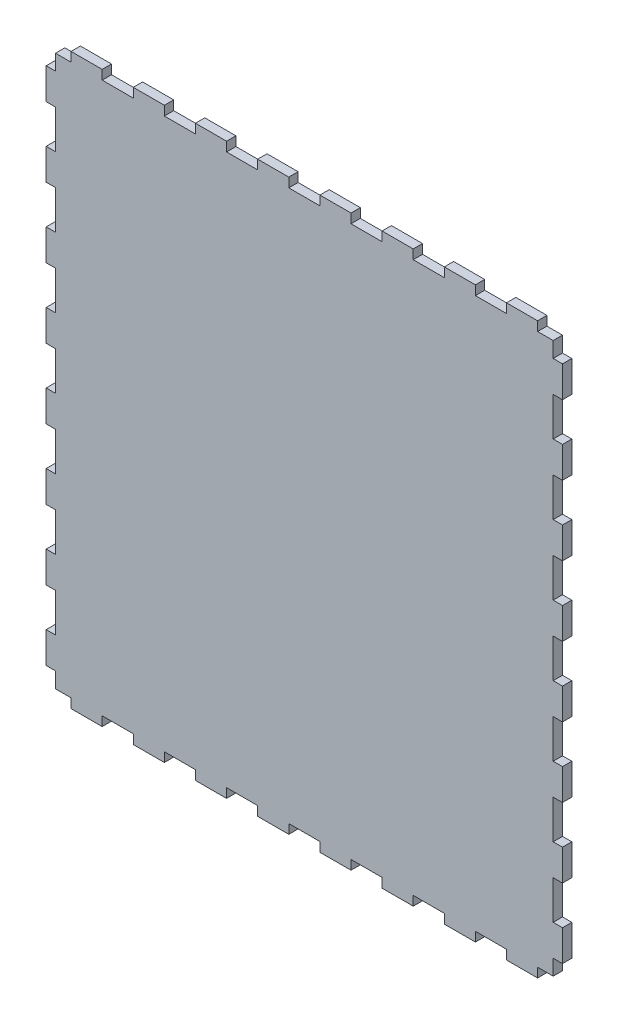
SolidWorks part; units mm, degrees
ref_plane "Front Plane" through (0, 0, 0) normal (0, 0, 1) x (1, 0, 0)
ref_plane "Top Plane" through (0, 0, 0) normal (0, 1, 0) x (1, 0, 0)
ref_plane "Right Plane" through (0, 0, 0) normal (1, 0, 0) x (0, 0, -1)
sketch "Sketch1" plane through (0, 0, 0) normal (0, 0, 1) x (1, 0, 0)
  line L0 (-39.6781, 48.7508) -> (-39.6781, 45.7508)
  line L1 (-64.6781, 45.7508) -> (-59.6781, 45.7508)
  line L2 (-64.6781, 45.7508) -> (-64.6781, 40.7508)
  line L3 (-64.6781, -131.2492) -> (-59.6781, -131.2492)
  line L4 (95.3219, 45.7508) -> (95.3219, 40.7508)
  line L5 (-59.6781, 48.7508) -> (-49.6781, 48.7508)
  line L6 (-59.6781, 48.7508) -> (-59.6781, 45.7508)
  line L8 (-49.6781, 48.7508) -> (-49.6781, 45.7508)
  line L9 (-39.6781, 48.7508) -> (-29.6781, 48.7508)
  line L10 (-29.6781, 48.7508) -> (-29.6781, 45.7508)
  line L12 (-19.6781, 48.7508) -> (-19.6781, 45.7508)
  line L13 (-19.6781, 48.7508) -> (-9.6781, 48.7508)
  line L14 (-9.6781, 48.7508) -> (-9.6781, 45.7508)
  line L16 (0.3219, 48.7508) -> (0.3219, 45.7508)
  line L17 (0.3219, 48.7508) -> (10.3219, 48.7508)
  line L18 (10.3219, 48.7508) -> (10.3219, 45.7508)
  line L20 (20.3219, 48.7508) -> (20.3219, 45.7508)
  line L21 (20.3219, 48.7508) -> (30.3219, 48.7508)
  line L22 (30.3219, 48.7508) -> (30.3219, 45.7508)
  line L24 (40.3219, 48.7508) -> (40.3219, 45.7508)
  line L25 (40.3219, 48.7508) -> (50.3219, 48.7508)
  line L26 (50.3219, 48.7508) -> (50.3219, 45.7508)
  line L28 (60.3219, 48.7508) -> (60.3219, 45.7508)
  line L29 (60.3219, 48.7508) -> (70.3219, 48.7508)
  line L30 (70.3219, 48.7508) -> (70.3219, 45.7508)
  line L32 (80.3219, 48.7508) -> (80.3219, 45.7508)
  line L33 (80.3219, 48.7508) -> (90.3219, 48.7508)
  line L34 (90.3219, 48.7508) -> (90.3219, 45.7508)
  line L37 (-64.6781, 40.7508) -> (-67.6781, 40.7508)
  line L39 (-64.6781, 30.7508) -> (-67.6781, 30.7508)
  line L40 (-67.6781, 40.7508) -> (-67.6781, 30.7508)
  line L41 (-64.6781, 18.3222) -> (-67.6781, 18.3222)
  line L42 (-67.6781, 18.3222) -> (-67.6781, 8.3222)
  line L43 (-64.6781, 8.3222) -> (-67.6781, 8.3222)
  line L45 (-64.6781, -4.1063) -> (-67.6781, -4.1063)
  line L46 (-67.6781, -4.1063) -> (-67.6781, -14.1063)
  line L47 (-64.6781, -14.1063) -> (-67.6781, -14.1063)
  line L49 (-64.6781, -26.5349) -> (-67.6781, -26.5349)
  line L50 (-67.6781, -26.5349) -> (-67.6781, -36.5349)
  line L51 (-64.6781, -36.5349) -> (-67.6781, -36.5349)
  line L53 (-64.6781, -48.9635) -> (-67.6781, -48.9635)
  line L54 (-67.6781, -48.9635) -> (-67.6781, -58.9635)
  line L55 (-64.6781, -58.9635) -> (-67.6781, -58.9635)
  line L57 (-64.6781, -71.3921) -> (-67.6781, -71.3921)
  line L58 (-67.6781, -71.3921) -> (-67.6781, -81.3921)
  line L59 (-64.6781, -81.3921) -> (-67.6781, -81.3921)
  line L61 (-64.6781, -93.8206) -> (-67.6781, -93.8206)
  line L62 (-67.6781, -93.8206) -> (-67.6781, -103.8206)
  line L63 (-64.6781, -103.8206) -> (-67.6781, -103.8206)
  line L65 (-64.6781, -116.2492) -> (-67.6781, -116.2492)
  line L66 (-67.6781, -116.2492) -> (-67.6781, -126.2492)
  line L67 (-64.6781, -126.2492) -> (-67.6781, -126.2492)
  line L68 (-39.6781, -134.2492) -> (-39.6781, -131.2492)
  line L69 (-59.6781, -134.2492) -> (-49.6781, -134.2492)
  line L70 (-59.6781, -134.2492) -> (-59.6781, -131.2492)
  line L72 (-49.6781, -134.2492) -> (-49.6781, -131.2492)
  line L73 (-39.6781, -134.2492) -> (-29.6781, -134.2492)
  line L74 (-29.6781, -134.2492) -> (-29.6781, -131.2492)
  line L76 (-19.6781, -134.2492) -> (-19.6781, -131.2492)
  line L77 (-19.6781, -134.2492) -> (-9.6781, -134.2492)
  line L78 (-9.6781, -134.2492) -> (-9.6781, -131.2492)
  line L80 (0.3219, -134.2492) -> (0.3219, -131.2492)
  line L81 (0.3219, -134.2492) -> (10.3219, -134.2492)
  line L82 (10.3219, -134.2492) -> (10.3219, -131.2492)
  line L84 (20.3219, -134.2492) -> (20.3219, -131.2492)
  line L85 (20.3219, -134.2492) -> (30.3219, -134.2492)
  line L86 (30.3219, -134.2492) -> (30.3219, -131.2492)
  line L88 (40.3219, -134.2492) -> (40.3219, -131.2492)
  line L89 (40.3219, -134.2492) -> (50.3219, -134.2492)
  line L90 (50.3219, -134.2492) -> (50.3219, -131.2492)
  line L92 (60.3219, -134.2492) -> (60.3219, -131.2492)
  line L93 (60.3219, -134.2492) -> (70.3219, -134.2492)
  line L94 (70.3219, -134.2492) -> (70.3219, -131.2492)
  line L96 (80.3219, -134.2492) -> (80.3219, -131.2492)
  line L97 (80.3219, -134.2492) -> (90.3219, -134.2492)
  line L98 (90.3219, -134.2492) -> (90.3219, -131.2492)
  line L101 (95.3219, 40.7508) -> (98.3219, 40.7508)
  line L103 (95.3219, 30.7508) -> (98.3219, 30.7508)
  line L104 (98.3219, 40.7508) -> (98.3219, 30.7508)
  line L105 (95.3219, 18.3222) -> (98.3219, 18.3222)
  line L106 (98.3219, 18.3222) -> (98.3219, 8.3222)
  line L107 (95.3219, 8.3222) -> (98.3219, 8.3222)
  line L109 (95.3219, -4.1063) -> (98.3219, -4.1063)
  line L110 (98.3219, -4.1063) -> (98.3219, -14.1063)
  line L111 (95.3219, -14.1063) -> (98.3219, -14.1063)
  line L113 (95.3219, -26.5349) -> (98.3219, -26.5349)
  line L114 (98.3219, -26.5349) -> (98.3219, -36.5349)
  line L115 (95.3219, -36.5349) -> (98.3219, -36.5349)
  line L117 (95.3219, -48.9635) -> (98.3219, -48.9635)
  line L118 (98.3219, -48.9635) -> (98.3219, -58.9635)
  line L119 (95.3219, -58.9635) -> (98.3219, -58.9635)
  line L121 (95.3219, -71.3921) -> (98.3219, -71.3921)
  line L122 (98.3219, -71.3921) -> (98.3219, -81.3921)
  line L123 (95.3219, -81.3921) -> (98.3219, -81.3921)
  line L125 (95.3219, -93.8206) -> (98.3219, -93.8206)
  line L126 (98.3219, -93.8206) -> (98.3219, -103.8206)
  line L127 (95.3219, -103.8206) -> (98.3219, -103.8206)
  line L129 (95.3219, -116.2492) -> (98.3219, -116.2492)
  line L130 (98.3219, -116.2492) -> (98.3219, -126.2492)
  line L131 (95.3219, -126.2492) -> (98.3219, -126.2492)
  line L132 (-49.6781, 45.7508) -> (-39.6781, 45.7508)
  line L133 (-29.6781, 45.7508) -> (-19.6781, 45.7508)
  line L134 (-9.6781, 45.7508) -> (0.3219, 45.7508)
  line L135 (30.3219, 45.7508) -> (40.3219, 45.7508)
  line L136 (10.3219, 45.7508) -> (20.3219, 45.7508)
  line L137 (50.3219, 45.7508) -> (60.3219, 45.7508)
  line L138 (70.3219, 45.7508) -> (80.3219, 45.7508)
  line L139 (90.3219, 45.7508) -> (95.3219, 45.7508)
  line L140 (95.3219, 30.7508) -> (95.3219, 18.3222)
  line L141 (95.3219, 8.3222) -> (95.3219, -4.1063)
  line L142 (95.3219, -14.1063) -> (95.3219, -26.5349)
  line L143 (95.3219, -36.5349) -> (95.3219, -48.9635)
  line L144 (95.3219, -58.9635) -> (95.3219, -71.3921)
  line L145 (95.3219, -81.3921) -> (95.3219, -93.8206)
  line L146 (95.3219, -103.8206) -> (95.3219, -116.2492)
  line L147 (95.3219, -126.2492) -> (95.3219, -131.2492)
  line L148 (90.3219, -131.2492) -> (95.3219, -131.2492)
  line L150 (70.3219, -131.2492) -> (80.3219, -131.2492)
  line L152 (50.3219, -131.2492) -> (60.3219, -131.2492)
  line L154 (30.3219, -131.2492) -> (40.3219, -131.2492)
  line L156 (10.3219, -131.2492) -> (20.3219, -131.2492)
  line L158 (-9.6781, -131.2492) -> (0.3219, -131.2492)
  line L160 (-29.6781, -131.2492) -> (-19.6781, -131.2492)
  line L162 (-49.6781, -131.2492) -> (-39.6781, -131.2492)
  line L163 (-64.6781, -126.2492) -> (-64.6781, -131.2492)
  line L165 (-64.6781, -103.8206) -> (-64.6781, -116.2492)
  line L167 (-64.6781, -81.3921) -> (-64.6781, -93.8206)
  line L169 (-64.6781, -58.9635) -> (-64.6781, -71.3921)
  line L171 (-64.6781, -36.5349) -> (-64.6781, -48.9635)
  line L173 (-64.6781, -14.1063) -> (-64.6781, -26.5349)
  line L175 (-64.6781, 8.3222) -> (-64.6781, -4.1063)
  line L177 (-64.6781, 30.7508) -> (-64.6781, 18.3222)
  point P104 (0, 0)
  point P105 (0, 0)
  point P134 (0, 0)
  dimension "D1" = 160
  dimension "D2" = 177
  dimension "D3" = 3
  dimension "D4" = 10
  dimension "D5" = 5
  dimension "D7" = 5
  dimension "D8" = 3
  dimension "D9" = 10
  dimension "D10" = 5
  dimension "D12" = 5
  dimension "D13" = 3
  dimension "D14" = 10
  dimension "D15" = 5
  dimension "D17" = 3
  dimension "D18" = 10
  dimension "D19" = 5
  dimension "D21" = 5
  dimension "D6" = 8
  dimension "D11" = 8
  dimension "D16" = 8
  dimension "D20" = 8
extrude "Boss-Extrude1" add sketch "Sketch1" along normal blind 3 contours L2 L37 L40 L39 L177 L41 L42 L43 L175 L45 L46 L47 L173 L49 L50 L51 L171 L53 L54 L55 L169 L57 L58 L59 L167 L61 L62 L63 L165 L65 L66 L67 L163 L3 L70 L69 L72 L162 L68 L73 L74 L160 L76 L77 L78 L158 L80 L81 L82 L156 L84 L85 L86 L154 L88 L89 L90 L152 L92 L93 L94 L150 L96 L97 L98 L148 L147 L131 L130 L129 L146 L127 L126 L125 L145 L123 L122 L121 L144 L119 L118 L117 L143 L115 L114 L113 L142 L111 L110 L109 L141 L107 L106 L105 L140 L103 L104 L101 L4 L139 L34 L33 L32 L138 L30 L29 L28 L137 L26 L25 L24 L135 L22 L21 L20 L136 L18 L17 L16 L134 L14 L13 L12 L133 L10 L9 L0 L132 L8 L5 L6 L1
